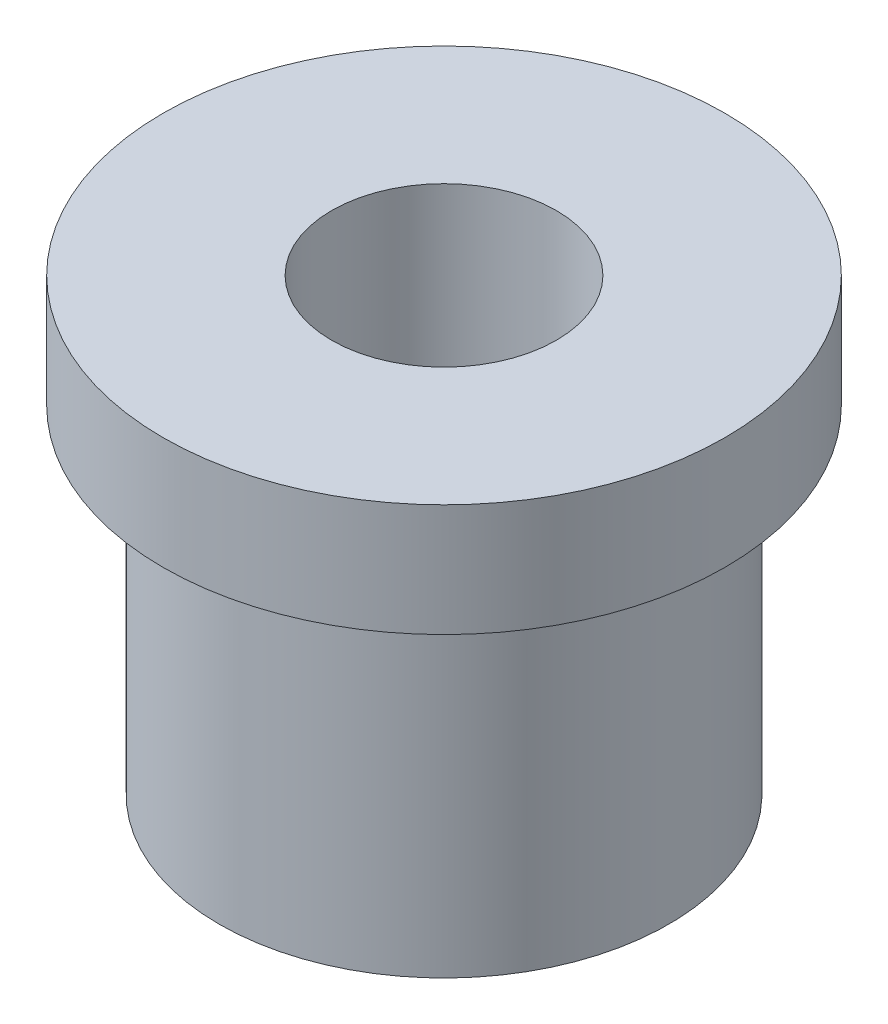
SolidWorks part; units mm, degrees
material "Plain Carbon Steel"
ref_plane "Front Plane" through (0, 0, 0) normal (0, 0, 1) x (1, 0, 0)
ref_plane "Top Plane" through (0, 0, 0) normal (0, 1, 0) x (1, 0, 0)
ref_plane "Right Plane" through (0, 0, 0) normal (1, 0, 0) x (0, 0, -1)
sketch "Sketch1" plane through (0, 0, 0) normal (0, 0, 1) x (1, 0, 0)
  line L0 (0, 0) -> (12.5, 0)
  line L1 (12.5, 0) -> (12.5, -5)
  line L2 (12.5, -5) -> (10, -5)
  line L3 (10, -5) -> (10, -20)
  line L4 (10, -20) -> (0, -20)
  line L5 (0, -20) -> (0, 0)
  line L6 (0, -25) -> (0, 5) construction
  dimension "D1" = 5
  dimension "D2" = 5
  dimension "D3" = 25
  dimension "D4" = 20
  dimension "D5" = 5
  dimension "D6" = 15
revolve "Revolve1" add sketch "Sketch1" angle 360 about L6
sketch "Sketch2" plane through (0, 0, 0) normal (0, 1, 0) x (1, 0, 0)
  circle A0 centre (0, 0) radius 5
  dimension "D1" = 10
extrude "Cut-Extrude1" cut sketch "Sketch2" against normal up to next
sketch "Sketch3" plane through (0, 0, 0) normal (0, 1, 0) x (1, 0, 0)
  line L0 (0, 10) -> (0, 0) construction
  line L1 (0, 0) -> (-8.6603, -5) construction
  line L2 (0, 0) -> (8.6603, -5) construction
  circle A0 centre (0, 0) radius 10 construction
  circle A1 centre (0, 10) radius 2.05
  circle A2 centre (8.6603, -5) radius 2.05
  circle A3 centre (-8.6603, -5) radius 2.05
  dimension "D1" = 20
  dimension "D4" = 4.1
  dimension "D2" = 120
  dimension "D3" = 120
